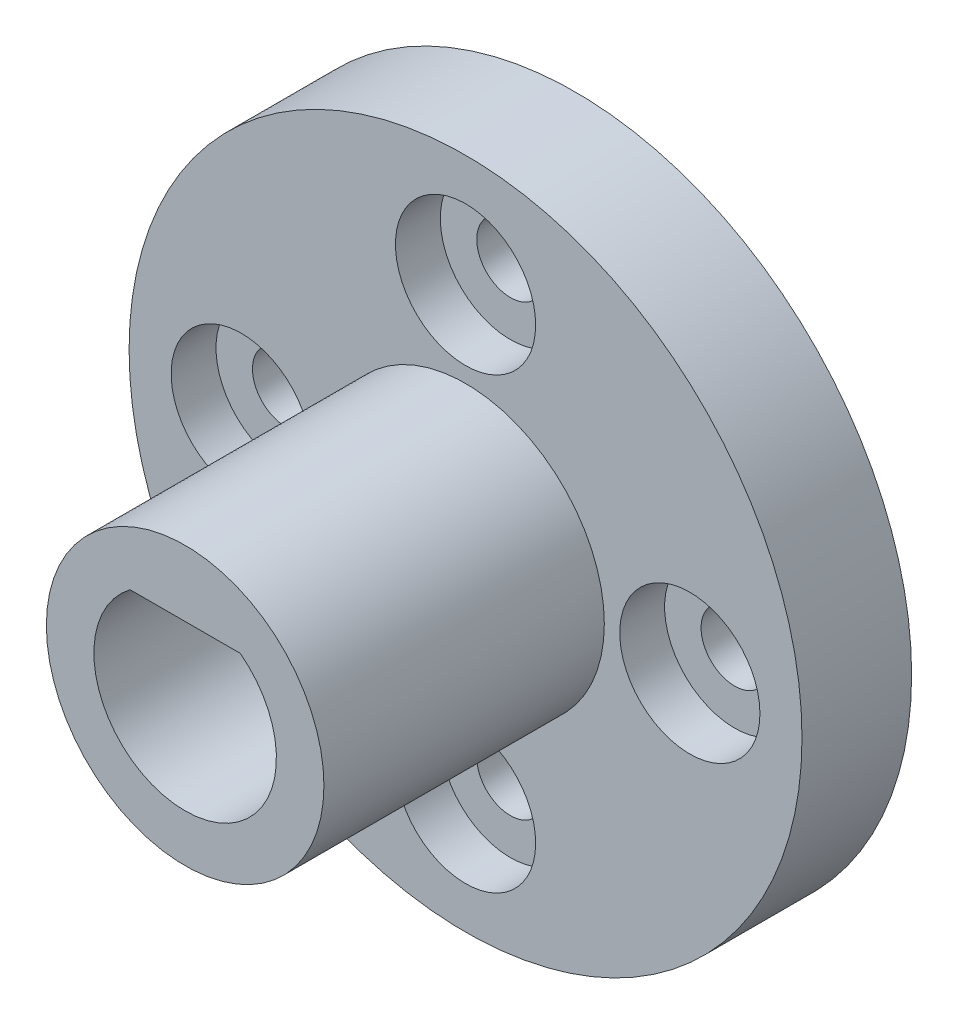
SolidWorks part; units mm, degrees
ref_plane "Plan de face" through (0, 0, 0) normal (0, 0, 1) x (1, 0, 0)
ref_plane "Plan de dessus" through (0, 0, 0) normal (0, 1, 0) x (1, 0, 0)
ref_plane "Plan de droite" through (0, 0, 0) normal (1, 0, 0) x (0, 0, -1)
sketch "Esquisse1" plane through (0, 0, 0) normal (0, 0, 1) x (1, 0, 0)
  circle A0 centre (0, 0) radius 12
  dimension "D1" = 24
extrude "Boss.-Extru.1" add sketch "Esquisse1" along normal blind 3.91
sketch "Esquisse6" plane through (0, 0, 0) normal (0, 0, -1) x (-1, 0, 0)
  circle A0 centre (0, 0) radius 4
  dimension "D1" = 8
extrude "Enlèv. mat.-Extru.2" cut sketch "Esquisse6" against normal blind 1.91
sketch "Esquisse7" plane through (0, 0, 3.91) normal (0, 0, 1) x (1, 0, 0)
  line L0 (1.9649, 2.595) -> (-1.9649, 2.595)
  line L1 (-5.4714, -3.255) -> (6.192, -3.255) construction
  arc A0 (-1.9649, 2.595) -> (1.9649, 2.595) centre (0, 0) ccw
  circle A1 centre (0, 0) radius 4.95
  dimension "D1" = 6.51
  dimension "D3" = 9.9
  dimension "D2" = 5.85
extrude "Boss.-Extru.2" add sketch "Esquisse7" along normal blind 10 contours A1 L1 A0 L0 | L1 A1
hole_wizard "Chambrage pour vis à tête ronde bombée M21" positions "Esquisse10" profile "Esquisse11" counterbore size "M2" standard "Ansi Metric" end condition through all
sketch "Esquisse10" plane through (0, 0, 3.91) normal (0, 0, 1) x (1, 0, 0)
  point P0 (0, 8)
  dimension "D1" = 8
sketch "Esquisse11" plane through (0, 8, 3.91) normal (1, 0, 0) x (0, -1, 0)
  line L0 (0, 0) -> (0, 3.91)
  line L1 (0, 3.91) -> (1.2, 3.91)
  line L3 (1.2, 3.91) -> (1.2, 1.6)
  line L4 (1.2, 1.6) -> (2.5, 1.6)
  line L5 (2.5, 1.6) -> (2.5, 0)
  line L7 (2.5, 0) -> (0, 0)
  line L11 (0, -6.35) -> (0, 107.95) construction
  dimension "Diamètre du perçage jusqu'au prochain" = 2.4
  dimension "Profondeur du perçage jusqu'au prochain" = 3.91
  dimension "Diamètre du chambrage" = 5
  dimension "Profondeur du chambrage" = 1.6
pattern_circular "Répétition circulaire2" count 4 every 90 about axis through (0, 0, 0) along (0, 0, 1) of "Chambrage pour vis à tête ronde bombée M21"
